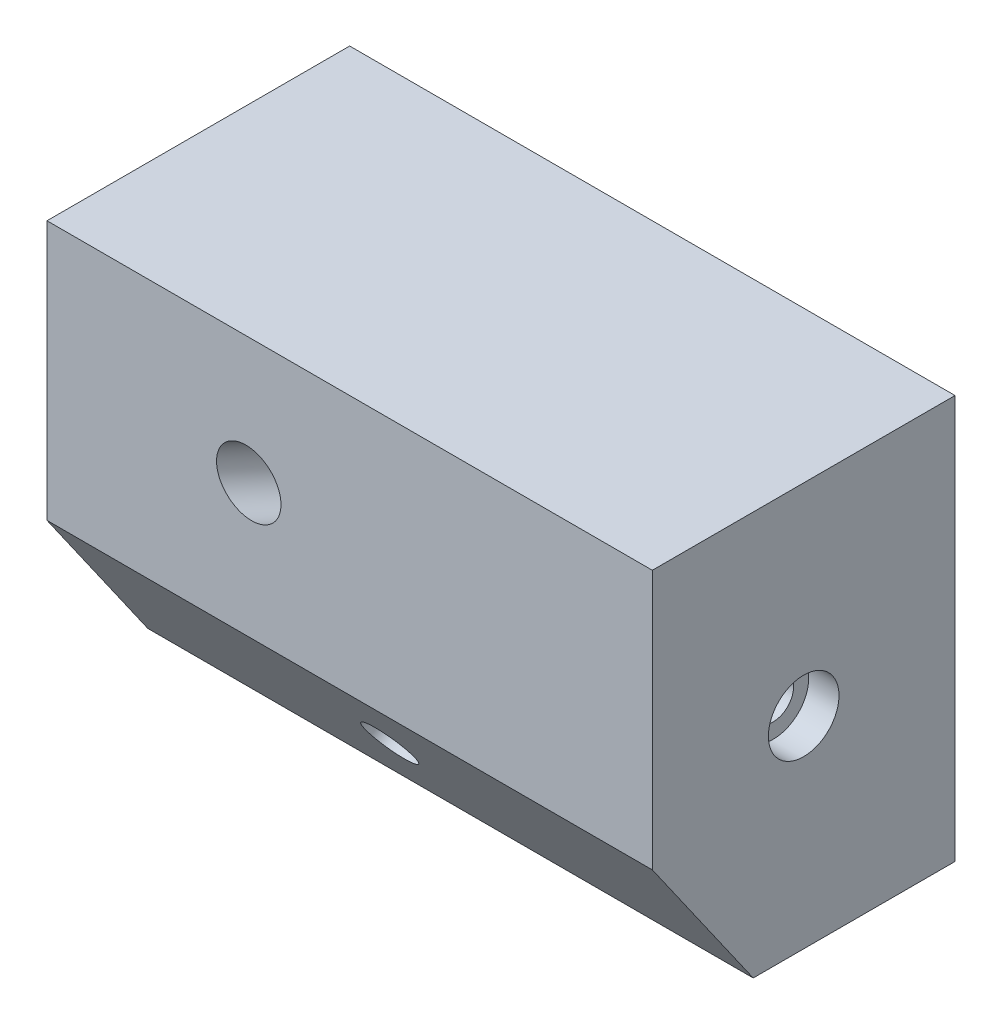
SolidWorks part; units mm, degrees
ref_plane "前视基准面" through (0, 0, 0) normal (0, 0, 1) x (1, 0, 0)
ref_plane "上视基准面" through (0, 0, 0) normal (0, 1, 0) x (1, 0, 0)
ref_plane "右视基准面" through (0, 0, 0) normal (1, 0, 0) x (0, 0, -1)
sketch "草图1" plane through (0, 0, 0) normal (0, 0, 1) x (1, 0, 0)
  line L0 (0, 0) -> (120, 0)
  line L1 (120, 0) -> (120, 80)
  line L2 (120, 80) -> (0, 80)
  line L3 (0, 80) -> (0, 0)
extrude "凸台-拉伸1" add sketch "草图1" along normal blind 60
sketch "草图2" plane through (0, 0, 0) normal (1, 0, 0) x (0, 0, -1)
  line L0 (-40, 0) -> (-60, 0)
  line L1 (-60, 0) -> (-60, 28.5629)
  line L2 (-60, 28.5629) -> (-40, 0)
extrude "切除-拉伸1" cut sketch "草图2" along normal through all
sketch3d "3D草图1"
  line L0 (36.6833, 57.4417, 69.1125) -> (58.9264, 41.0666, 8)
sweep "切除-扫描2" cut path "3D草图1" circular profile diameter 12 parameters "D3"=12
sketch "草图4" plane through (0.7386, -0.5437, -2.0292) normal (-0.3317, 0.2442, 0.9113) x (0.9434, 0.0858, 0.3204)
  arc A0 (61.6792, 31.5968) -> (61.6792, 43.5968) centre (61.6792, 37.5968) cw
  arc A1 (61.6792, 43.5968) -> (61.6792, 31.5968) centre (61.6792, 37.5968) cw
extrude "切除-拉伸2" cut sketch "草图4" against normal blind 3.6022 draft 59
ref_plane "基准面1" through (120, 0, 0) normal (1, 0, 0) x (0, 0, -1)
sketch "草图5" plane through (120, 0, 0) normal (1, 0, 0) x (0, 0, -1)
  circle A0 centre (-30, 40) radius 7
extrude "切除-拉伸3" cut sketch "草图5" against normal blind 6
sketch "草图6" plane through (120, 0, 0) normal (1, 0, 0) x (0, 0, -1)
  circle A0 centre (-30, 40) radius 4
extrude "切除-拉伸4" cut sketch "草图6" against normal blind 50
sketch3d "3D草图2"
  line L0 (57.9403, 8.5457, 58.1915) -> (57.9403, 41.7927, 10.7099)
sweep "切除-扫描4" cut path "3D草图2" circular profile diameter 10 parameters "D3"=10
